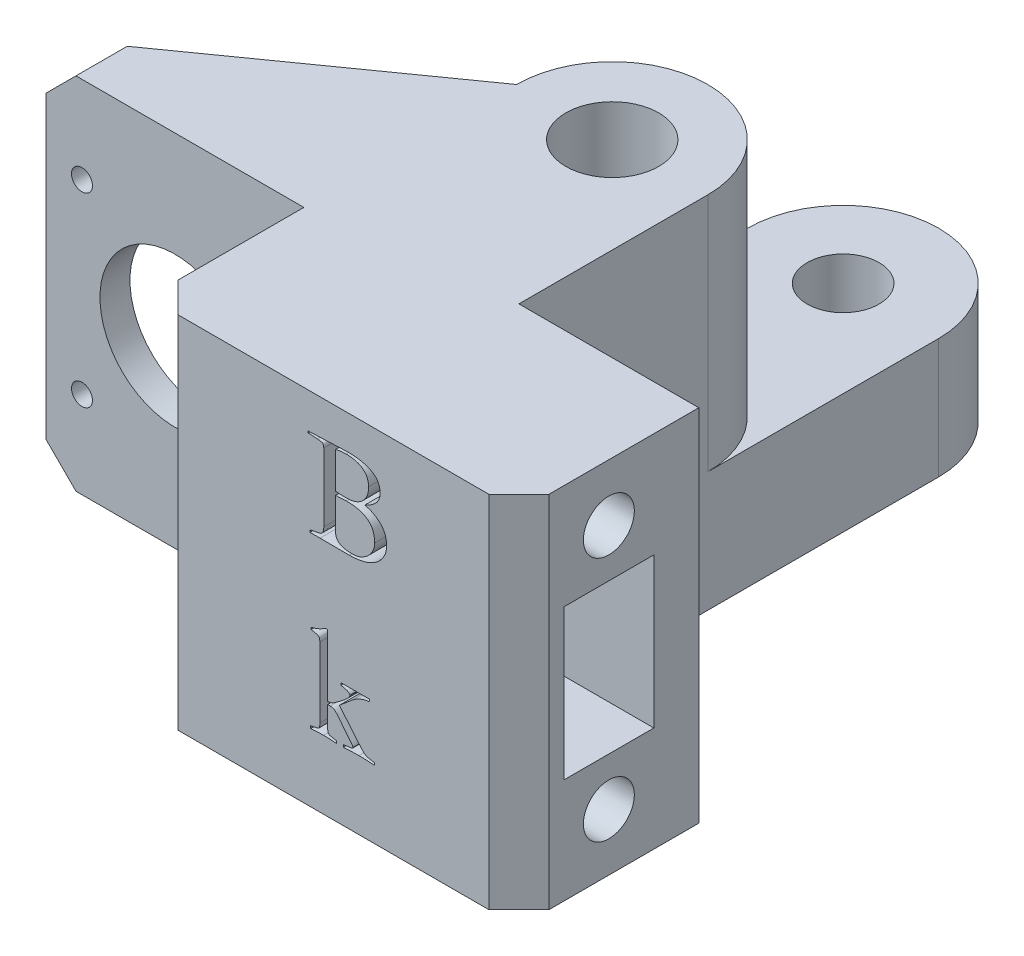
SolidWorks part; units mm, degrees
ref_plane "前视基准面" through (0, 0, 0) normal (0, 0, 1) x (1, 0, 0)
ref_plane "上视基准面" through (0, 0, 0) normal (0, 1, 0) x (1, 0, 0)
ref_plane "右视基准面" through (0, 0, 0) normal (1, 0, 0) x (0, 0, -1)
sketch "草图1" plane through (0, 0, 0) normal (0, 1, 0) x (1, 0, 0)
  line L11 (74.5174, 16.1852) -> (74.5174, -83.8148)
  line L12 (74.5174, -83.8148) -> (106.3833, -83.8148)
  line L13 (106.3833, -83.8148) -> (106.3833, 16.1852)
  line L15 (90.4503, -22.1888) -> (90.4503, -83.8148) construction
  circle A3 centre (90.4503, 16.1852) radius 6
  circle A4 centre (90.4503, -22.3148) radius 7.75
  arc A5 (74.5174, 16.1852) -> (106.3833, 16.1852) centre (90.4503, 16.1852) cw
  dimension "D7" = 12
  dimension "D8" = 15.5
  dimension "D6" = 100
  dimension "D9" = 38.5
extrude "凸台-拉伸1" add sketch "草图1" along normal blind 60
sketch "草图3" plane through (0, 60, 0) normal (0, 1, 0) x (1, 0, 0)
  circle A0 centre (90.4503, 16.1852) radius 15.9329
extrude "切除-拉伸1" cut sketch "草图3" against normal blind 40
sketch "草图4" plane through (0, 60, 0) normal (0, 1, 0) x (1, 0, 0)
  line L0 (74.5174, 16.1852) -> (74.5174, -22.3148)
  line L1 (106.3833, 16.1852) -> (106.3833, -22.3148)
  line L2 (74.5174, 16.1852) -> (106.3833, 16.1852)
  arc A0 (106.3833, -22.3148) -> (74.5174, -22.3148) centre (90.4503, -22.3148) ccw
extrude "切除-拉伸2" cut sketch "草图4" against normal blind 40
sketch "草图5" plane through (74.5174, 0, 0) normal (-1, 0, 0) x (0, 0, 1)
  line L0 (68.8148, 0) -> (68.8148, 60) construction
  line L1 (-16.1852, 0) -> (83.8148, 0) construction
  line L2 (22.3148, 60) -> (83.8148, 60) construction
  circle A0 centre (68.8148, 9.5) radius 4.25
  circle A1 centre (68.8148, 50.5) radius 4.25
  point P10 (68.8148, 30)
  dimension "D4" = 8.5
  dimension "D5" = 8.5
  dimension "D1" = 15
  dimension "D2" = 20.5
  dimension "D3" = 20.5
extrude "切除-拉伸3" cut sketch "草图5" against normal through all
sketch "草图6" plane through (106.3833, 0, 0) normal (1, 0, 0) x (0, 0, -1)
  line L0 (-83.8148, 60) -> (-53.8148, 60)
  line L1 (-83.8148, 60) -> (-22.3148, 60) construction
  line L2 (-53.8148, 60) -> (-53.8148, 0)
  line L3 (-83.8148, 0) -> (16.1852, 0) construction
  line L4 (-53.8148, 0) -> (-83.8148, 0)
  line L5 (-83.8148, 0) -> (-83.8148, 60)
  circle A0 centre (-68.8148, 50.5) radius 4.25 construction
  circle A1 centre (-68.8148, 50.5) radius 4.25
  circle A2 centre (-68.8148, 9.5) radius 4.25 construction
  circle A3 centre (-68.8148, 9.5) radius 4.25
  dimension "D1" = 30
extrude "凸台-拉伸2" add sketch "草图6" along normal blind 30
sketch "草图7" plane through (74.5174, 0, 0) normal (-1, 0, 0) x (0, 0, 1)
  line L0 (68.8148, 50.5) -> (68.8148, 9.5) construction
  line L2 (61.3148, 42.5) -> (76.3148, 42.5)
  line L3 (61.3148, 42.5) -> (61.3148, 17.5)
  line L4 (61.3148, 17.5) -> (76.3148, 17.5)
  line L5 (76.3148, 42.5) -> (76.3148, 17.5)
  line L6 (68.8148, 17.5) -> (68.8148, 42.5) construction
  line L7 (61.3148, 30) -> (76.3148, 30) construction
  point P4 (68.8148, 30)
  dimension "D1" = 15
  dimension "D2" = 25
extrude "切除-拉伸4" cut sketch "草图7" against normal through all
sketch "草图8" plane through (74.5174, 0, 0) normal (-1, 0, 0) x (0, 0, 1)
  line L0 (52.8148, 0) -> (52.8148, 60)
  line L1 (-16.1852, 0) -> (83.8148, 0) construction
  line L2 (22.3148, 60) -> (83.8148, 60) construction
  line L3 (52.8148, 60) -> (57.8148, 60)
  line L4 (57.8148, 60) -> (57.8148, 0)
  line L5 (57.8148, 0) -> (52.8148, 0)
  line L8 (83.8148, 60) -> (83.8148, 0) construction
  dimension "D1" = 5
  dimension "D2" = 31
extrude "凸台-拉伸3" add sketch "草图8" along normal blind 43
sketch "草图9" plane through (0, 0, 57.8148) normal (0, 0, 1) x (1, 0, 0)
  line L0 (53.0174, 60) -> (53.0174, 0) construction
  line L1 (31.5174, 60) -> (74.5174, 60) construction
  line L2 (31.5174, 0) -> (74.5174, 0) construction
  line L4 (37.5174, 45.5) -> (68.5174, 45.5) construction
  line L5 (37.5174, 45.5) -> (37.5174, 14.5) construction
  line L6 (37.5174, 14.5) -> (68.5174, 14.5) construction
  line L7 (68.5174, 45.5) -> (68.5174, 14.5) construction
  line L8 (53.0174, 14.5) -> (53.0174, 45.5) construction
  line L9 (37.5174, 30) -> (68.5174, 30) construction
  circle A1 centre (53.0174, 30) radius 12.5
  circle A2 centre (68.5174, 45.5) radius 1.75
  circle A3 centre (37.5174, 45.5) radius 1.75
  circle A4 centre (37.5174, 14.5) radius 1.75
  circle A5 centre (68.5174, 14.5) radius 1.75
  dimension "D1" = 25
  dimension "D4" = 3.5
  dimension "D2" = 31
  dimension "D3" = 31
extrude "切除-拉伸5" cut sketch "草图9" against normal through all
sketch "草图10" plane through (0, 60, 0) normal (0, 1, 0) x (1, 0, 0)
  line L0 (31.5174, -52.8148) -> (74.5174, -52.8148)
  line L1 (74.5174, -52.8148) -> (74.5174, -22.3148)
  line L2 (74.5174, -22.3148) -> (31.5174, -52.8148)
extrude "凸台-拉伸4" add sketch "草图10" against normal blind 5
sketch "草图12" plane through (0, 0, 0) normal (0, -1, 0) x (1, 0, 0)
  line L3 (31.5174, 52.8148) -> (74.5174, 22.3148)
  line L4 (74.5174, 22.3148) -> (74.5174, 52.8148)
  line L5 (74.5174, 52.8148) -> (31.5174, 52.8148)
  line L6 (31.5174, 52.8148) -> (74.5174, 22.3148)
  line L7 (74.5174, 22.3148) -> (74.5174, 52.8148)
  line L8 (74.5174, 52.8148) -> (31.5174, 52.8148)
  dimension "D1" = 0
extrude "凸台-拉伸5" add sketch "草图12" against normal blind 5
chamfer "倒角1" distance 5 angle 45 2 edges at (136.3833, 30, 83.8148) (74.5174, 30, 83.8148)
chamfer "倒角2" distance 5 angle 45 2 edges at (31.5174, 0, 55.3148) (31.5174, 60, 55.3148)
sketch "草图13" plane through (0, 0, 83.8148) normal (0, 0, 1) x (1, 0, 0)
  text T0 "B\r\nk" font "华文楷体" height 15
extrude "切除-拉伸6" cut sketch "草图13" against normal blind 5
